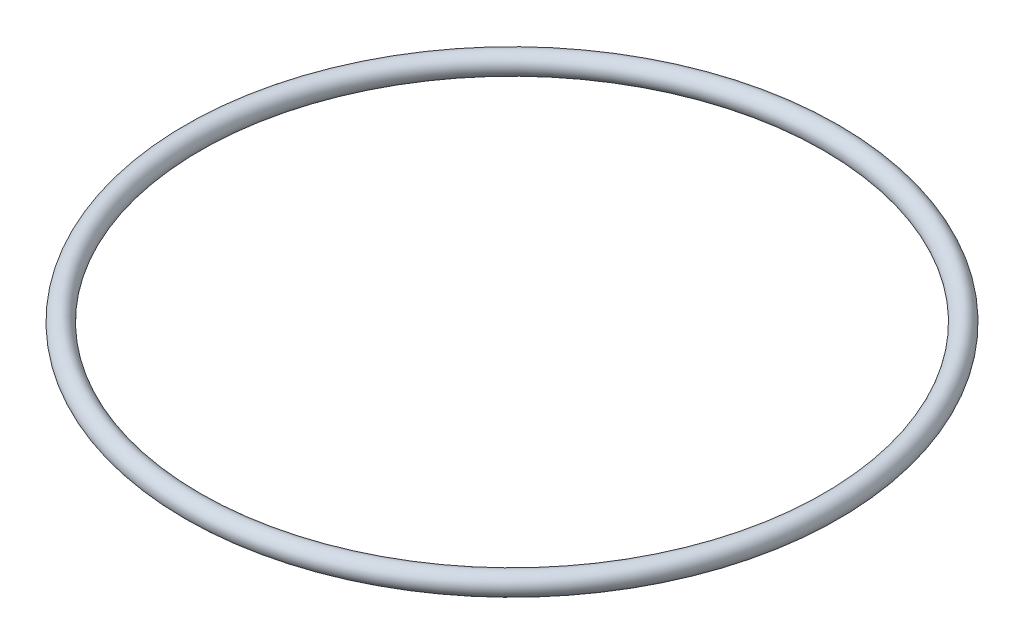
SolidWorks part; units mm, degrees
material "BUTYL"
ref_plane "Plano frontal" through (0, 0, 0) normal (0, 0, 1) x (1, 0, 0)
ref_plane "Plano superior" through (0, 0, 0) normal (0, 1, 0) x (1, 0, 0)
ref_plane "Plano direito" through (0, 0, 0) normal (1, 0, 0) x (0, 0, -1)
sketch "Esboço1" plane through (0, 0, 0) normal (0, 0, 1) x (1, 0, 0)
  line L0 (0, 0) -> (0, 87.2738) construction
  circle A0 centre (-53.95, 0) radius 1.765
  point P5 (-52.185, 0)
  dimension "D2" = 3.53
  dimension "D1" = 52.185
revolve "Revolução1" add sketch "Esboço1" angle 360 about L0
sketch "Esboço2" plane through (0, 0, 0) normal (0, 1, 0) x (1, 0, 0)
  circle A0 centre (0, 0) radius 30.004
